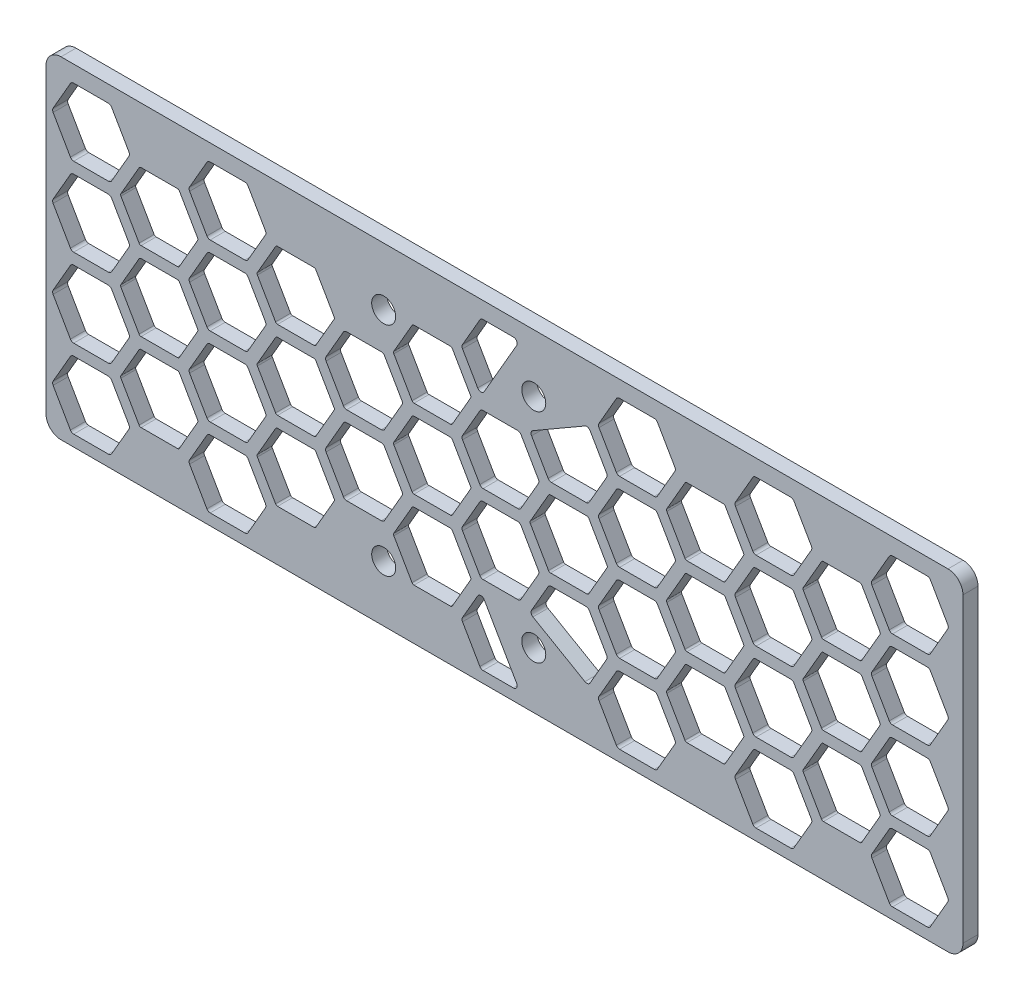
SolidWorks part; units mm, degrees
material "Thornel Mat VMA"
ref_plane "前视基准面" through (0, 0, 0) normal (0, 0, 1) x (1, 0, 0)
ref_plane "上视基准面" through (0, 0, 0) normal (0, 1, 0) x (1, 0, 0)
ref_plane "右视基准面" through (0, 0, 0) normal (1, 0, 0) x (0, 0, -1)
sketch "草图2" plane through (0, 0, 0) normal (0, 0, 1) x (1, 0, 0)
  line L89 (-79.335, -36.7) -> (-79.335, 7.5)
  line L90 (-79.335, 7.5) -> (42.865, 7.5)
  line L91 (42.865, 7.5) -> (42.865, -36.7)
  line L92 (-79.335, -36.7) -> (42.865, -36.7)
  line L120 (-41.8743, -0.2) -> (-5.6722, -0.2) construction
  line L121 (-40.735, -29.2) -> (-8.6619, -29.2) construction
  line L125 (-77.335, 3.8) -> (40.665, 3.8) construction
  line L126 (-77.335, -33.2) -> (40.665, -33.2) construction
  circle A0 centre (-34.335, -0.2) radius 1.6
  circle A1 centre (-14.335, -0.2) radius 1.6
  circle A2 centre (-34.335, -29.2) radius 1.6
  circle A3 centre (-14.335, -29.2) radius 1.6
  point P5 (-79.335, -14.6)
  point P13 (-79.335, -14.6)
  dimension "D1" = 44.2
  dimension "D19" = 4
  dimension "D21" = 20
  dimension "D22" = 20
  dimension "D23" = 45
  dimension "D24" = 45
  dimension "D25" = 3.2
  dimension "D26" = 3.2
  dimension "D27" = 3.2
  dimension "D28" = 3.2
  dimension "D2" = 122.2
  dimension "D20" = 4
extrude "凸台-拉伸1" add sketch "草图2" along normal blind 2
sketch "草图3" plane through (0, 0, 2) normal (0, 0, 1) x (1, 0, 0)
  line L0 (-79.335, -36.7) -> (42.865, -36.7) construction
  line L1 (30.7324, -20.45) -> (33.0418, -24.45)
  line L2 (33.4748, -24.7) -> (38.0936, -24.7)
  line L3 (-78.3868, -30.95) -> (-76.0774, -34.95)
  line L4 (-75.6444, -35.2) -> (-71.0256, -35.2)
  line L5 (-70.5925, -34.95) -> (-68.2831, -30.95)
  line L100 (-68.2831, -30.45) -> (-70.5925, -26.45)
  line L101 (-71.0256, -26.2) -> (-75.6444, -26.2)
  line L102 (-76.0774, -26.45) -> (-78.3868, -30.45)
  line L103 (-79.335, 7.5) -> (-79.335, -36.7) construction
  line L104 (-78.3868, -20.45) -> (-76.0774, -24.45)
  line L105 (-75.6444, -24.7) -> (-71.0256, -24.7)
  line L106 (-70.5925, -24.45) -> (-68.2831, -20.45)
  line L107 (-68.2831, -19.95) -> (-70.5925, -15.95)
  line L108 (-71.0256, -15.7) -> (-75.6444, -15.7)
  line L109 (-76.0774, -15.95) -> (-78.3868, -19.95)
  line L110 (-78.3868, -9.95) -> (-76.0774, -13.95)
  line L111 (-75.6444, -14.2) -> (-71.0256, -14.2)
  line L112 (-70.5925, -13.95) -> (-68.2831, -9.95)
  line L113 (-68.2831, -9.45) -> (-70.5925, -5.45)
  line L114 (-71.0256, -5.2) -> (-75.6444, -5.2)
  line L115 (-76.0774, -5.45) -> (-78.3868, -9.45)
  line L116 (-78.3868, 0.55) -> (-76.0774, -3.45)
  line L117 (-75.6444, -3.7) -> (-71.0256, -3.7)
  line L118 (-70.5925, -3.45) -> (-68.2831, 0.55)
  line L119 (-68.2831, 1.05) -> (-70.5925, 5.05)
  line L120 (-71.0256, 5.3) -> (-75.6444, 5.3)
  line L121 (-76.0774, 5.05) -> (-78.3868, 1.05)
  line L128 (-69.3504, -15.1015) -> (-66.9272, -19.2985)
  line L129 (-69.3504, -25.6015) -> (-66.9272, -29.7985)
  line L130 (-66.6648, -29.95) -> (-61.8186, -29.95)
  line L131 (-61.5561, -29.7985) -> (-59.133, -25.6015)
  line L132 (-59.133, -25.2985) -> (-61.5561, -21.1015)
  line L133 (-61.8186, -20.95) -> (-66.6648, -20.95)
  line L134 (-66.9272, -21.1015) -> (-69.3504, -25.2985)
  line L135 (-66.6648, -19.45) -> (-61.8186, -19.45)
  line L136 (-61.5561, -19.2985) -> (-59.133, -15.1015)
  line L137 (-59.133, -14.7985) -> (-61.5561, -10.6015)
  line L138 (-61.8186, -10.45) -> (-66.6648, -10.45)
  line L139 (-66.9272, -10.6015) -> (-69.3504, -14.7985)
  line L140 (-69.3504, -4.6015) -> (-66.9272, -8.7985)
  line L141 (-66.6648, -8.95) -> (-61.8186, -8.95)
  line L142 (-61.5561, -8.7985) -> (-59.133, -4.6015)
  line L143 (-59.133, -4.2985) -> (-61.5561, -0.1015)
  line L144 (-61.8186, 0.05) -> (-66.6648, 0.05)
  line L145 (-66.9272, -0.1015) -> (-69.3504, -4.2985)
  line L146 (-60.2002, -30.95) -> (-57.8908, -34.95)
  line L147 (-57.4578, -35.2) -> (-52.839, -35.2)
  line L148 (-52.406, -34.95) -> (-50.0966, -30.95)
  line L149 (-50.0966, -30.45) -> (-52.406, -26.45)
  line L150 (-52.839, -26.2) -> (-57.4578, -26.2)
  line L151 (-57.8908, -26.45) -> (-60.2002, -30.45)
  line L152 (-60.2002, -20.45) -> (-57.8908, -24.45)
  line L153 (-57.4578, -24.7) -> (-52.839, -24.7)
  line L154 (-52.406, -24.45) -> (-50.0966, -20.45)
  line L155 (-50.0966, -19.95) -> (-52.406, -15.95)
  line L156 (-52.839, -15.7) -> (-57.4578, -15.7)
  line L157 (-57.8908, -15.95) -> (-60.2002, -19.95)
  line L158 (-60.2002, -9.95) -> (-57.8908, -13.95)
  line L159 (-57.4578, -14.2) -> (-52.839, -14.2)
  line L160 (-52.406, -13.95) -> (-50.0966, -9.95)
  line L161 (-50.0966, -9.45) -> (-52.406, -5.45)
  line L162 (-52.839, -5.2) -> (-57.4578, -5.2)
  line L163 (-57.8908, -5.45) -> (-60.2002, -9.45)
  line L164 (-60.2002, 0.55) -> (-57.8908, -3.45)
  line L165 (-57.4578, -3.7) -> (-52.839, -3.7)
  line L166 (-52.406, -3.45) -> (-50.0966, 0.55)
  line L167 (-50.0966, 1.05) -> (-52.406, 5.05)
  line L168 (-52.839, 5.3) -> (-57.4578, 5.3)
  line L169 (-57.8908, 5.05) -> (-60.2002, 1.05)
  line L170 (-51.1638, -15.1015) -> (-48.7407, -19.2985)
  line L171 (-51.1638, -25.6015) -> (-48.7407, -29.7985)
  line L172 (-48.4783, -29.95) -> (-43.632, -29.95)
  line L173 (-43.3696, -29.7985) -> (-40.9465, -25.6015)
  line L174 (-40.9465, -25.2985) -> (-43.3696, -21.1015)
  line L175 (-43.632, -20.95) -> (-48.4783, -20.95)
  line L176 (-48.7407, -21.1015) -> (-51.1638, -25.2985)
  line L177 (-48.4783, -19.45) -> (-43.632, -19.45)
  line L178 (-43.3696, -19.2985) -> (-40.9465, -15.1015)
  line L179 (-40.9465, -14.7985) -> (-43.3696, -10.6015)
  line L180 (-43.632, -10.45) -> (-48.4783, -10.45)
  line L181 (-48.7407, -10.6015) -> (-51.1638, -14.7985)
  line L182 (-51.1638, -4.6015) -> (-48.7407, -8.7985)
  line L183 (-48.4783, -8.95) -> (-43.632, -8.95)
  line L184 (-43.3696, -8.7985) -> (-40.9465, -4.6015)
  line L185 (-40.9465, -4.2985) -> (-43.3696, -0.1015)
  line L186 (-43.632, 0.05) -> (-48.4783, 0.05)
  line L187 (-48.7407, -0.1015) -> (-51.1638, -4.2985)
  line L194 (-42.0137, -20.45) -> (-39.7043, -24.45)
  line L195 (-39.2713, -24.7) -> (-34.6525, -24.7)
  line L196 (-34.2195, -24.45) -> (-31.9101, -20.45)
  line L197 (-31.9101, -19.95) -> (-34.2195, -15.95)
  line L198 (-34.6525, -15.7) -> (-39.2713, -15.7)
  line L199 (-39.7043, -15.95) -> (-42.0137, -19.95)
  line L200 (-42.0137, -9.95) -> (-39.7043, -13.95)
  line L201 (-39.2713, -14.2) -> (-34.6525, -14.2)
  line L202 (-34.2195, -13.95) -> (-31.9101, -9.95)
  line L203 (-31.9101, -9.45) -> (-34.2195, -5.45)
  line L204 (-34.6525, -5.2) -> (-39.2713, -5.2)
  line L205 (-39.7043, -5.45) -> (-42.0137, -9.45)
  line L212 (-32.9773, -15.1015) -> (-30.5542, -19.2985)
  line L213 (-32.9773, -25.6015) -> (-30.5542, -29.7985)
  line L214 (-30.2918, -29.95) -> (-25.4455, -29.95)
  line L215 (-25.1831, -29.7985) -> (-22.7599, -25.6015)
  line L216 (-22.7599, -25.2985) -> (-25.1831, -21.1015)
  line L217 (-25.4455, -20.95) -> (-30.2918, -20.95)
  line L218 (-30.5542, -21.1015) -> (-32.9773, -25.2985)
  line L219 (-30.2918, -19.45) -> (-25.4455, -19.45)
  line L220 (-25.1831, -19.2985) -> (-22.7599, -15.1015)
  line L221 (-22.7599, -14.7985) -> (-25.1831, -10.6015)
  line L222 (-25.4455, -10.45) -> (-30.2918, -10.45)
  line L223 (-30.5542, -10.6015) -> (-32.9773, -14.7985)
  line L224 (-32.9773, -4.6015) -> (-30.5542, -8.7985)
  line L225 (-30.2918, -8.95) -> (-25.4455, -8.95)
  line L226 (-25.1831, -8.7985) -> (-22.7599, -4.6015)
  line L227 (-22.7599, -4.2985) -> (-25.1831, -0.1015)
  line L228 (-25.4455, 0.05) -> (-30.2918, 0.05)
  line L229 (-30.5542, -0.1015) -> (-32.9773, -4.2985)
  line L236 (-23.8272, -20.45) -> (-21.5178, -24.45)
  line L237 (-21.0848, -24.7) -> (-16.466, -24.7)
  line L238 (-16.0329, -24.45) -> (-13.7235, -20.45)
  line L239 (-13.7235, -19.95) -> (-16.0329, -15.95)
  line L240 (-16.466, -15.7) -> (-21.0848, -15.7)
  line L241 (-21.5178, -15.95) -> (-23.8272, -19.95)
  line L242 (-23.8272, -9.95) -> (-21.5178, -13.95)
  line L243 (-21.0848, -14.2) -> (-16.466, -14.2)
  line L244 (-16.0329, -13.95) -> (-13.7235, -9.95)
  line L245 (-13.7235, -9.45) -> (-16.0329, -5.45)
  line L246 (-16.466, -5.2) -> (-21.0848, -5.2)
  line L247 (-21.5178, -5.45) -> (-23.8272, -9.45)
  line L254 (-14.7908, -15.1015) -> (-12.3676, -19.2985)
  line L261 (-12.1052, -19.45) -> (-7.259, -19.45)
  line L262 (-6.9965, -19.2985) -> (-4.5734, -15.1015)
  line L263 (-4.5734, -14.7985) -> (-6.9965, -10.6015)
  line L264 (-7.259, -10.45) -> (-12.1052, -10.45)
  line L265 (-12.3676, -10.6015) -> (-14.7908, -14.7985)
  line L272 (-5.6406, -30.95) -> (-3.3312, -34.95)
  line L273 (-2.8982, -35.2) -> (1.7206, -35.2)
  line L274 (2.1536, -34.95) -> (4.463, -30.95)
  line L275 (4.463, -30.45) -> (2.1536, -26.45)
  line L276 (1.7206, -26.2) -> (-2.8982, -26.2)
  line L277 (-3.3312, -26.45) -> (-5.6406, -30.45)
  line L278 (-5.6406, -20.45) -> (-3.3312, -24.45)
  line L279 (-2.8982, -24.7) -> (1.7206, -24.7)
  line L280 (2.1536, -24.45) -> (4.463, -20.45)
  line L281 (4.463, -19.95) -> (2.1536, -15.95)
  line L282 (1.7206, -15.7) -> (-2.8982, -15.7)
  line L283 (-3.3312, -15.95) -> (-5.6406, -19.95)
  line L284 (-5.6406, -9.95) -> (-3.3312, -13.95)
  line L285 (-2.8982, -14.2) -> (1.7206, -14.2)
  line L286 (2.1536, -13.95) -> (4.463, -9.95)
  line L287 (4.463, -9.45) -> (2.1536, -5.45)
  line L288 (1.7206, -5.2) -> (-2.8982, -5.2)
  line L289 (-3.3312, -5.45) -> (-5.6406, -9.45)
  line L290 (-5.6406, 0.55) -> (-3.3312, -3.45)
  line L291 (-2.8982, -3.7) -> (1.7206, -3.7)
  line L292 (2.1536, -3.45) -> (4.463, 0.55)
  line L293 (4.463, 1.05) -> (2.1536, 5.05)
  line L294 (1.7206, 5.3) -> (-2.8982, 5.3)
  line L295 (-3.3312, 5.05) -> (-5.6406, 1.05)
  line L296 (3.3958, -15.1015) -> (5.8189, -19.2985)
  line L297 (3.3958, -25.6015) -> (5.8189, -29.7985)
  line L298 (6.0813, -29.95) -> (10.9276, -29.95)
  line L299 (11.19, -29.7985) -> (13.6131, -25.6015)
  line L300 (13.6131, -25.2985) -> (11.19, -21.1015)
  line L301 (10.9276, -20.95) -> (6.0813, -20.95)
  line L302 (5.8189, -21.1015) -> (3.3958, -25.2985)
  line L303 (6.0813, -19.45) -> (10.9276, -19.45)
  line L304 (11.19, -19.2985) -> (13.6131, -15.1015)
  line L305 (13.6131, -14.7985) -> (11.19, -10.6015)
  line L306 (10.9276, -10.45) -> (6.0813, -10.45)
  line L307 (5.8189, -10.6015) -> (3.3958, -14.7985)
  line L308 (3.3958, -4.6015) -> (5.8189, -8.7985)
  line L309 (6.0813, -8.95) -> (10.9276, -8.95)
  line L310 (11.19, -8.7985) -> (13.6131, -4.6015)
  line L311 (13.6131, -4.2985) -> (11.19, -0.1015)
  line L312 (10.9276, 0.05) -> (6.0813, 0.05)
  line L313 (5.8189, -0.1015) -> (3.3958, -4.2985)
  line L314 (12.5459, -30.95) -> (14.8553, -34.95)
  line L315 (15.2883, -35.2) -> (19.9071, -35.2)
  line L316 (20.3401, -34.95) -> (22.6495, -30.95)
  line L317 (22.6495, -30.45) -> (20.3401, -26.45)
  line L318 (19.9071, -26.2) -> (15.2883, -26.2)
  line L319 (14.8553, -26.45) -> (12.5459, -30.45)
  line L320 (12.5459, -20.45) -> (14.8553, -24.45)
  line L321 (15.2883, -24.7) -> (19.9071, -24.7)
  line L322 (20.3401, -24.45) -> (22.6495, -20.45)
  line L323 (22.6495, -19.95) -> (20.3401, -15.95)
  line L324 (19.9071, -15.7) -> (15.2883, -15.7)
  line L325 (14.8553, -15.95) -> (12.5459, -19.95)
  line L326 (12.5459, -9.95) -> (14.8553, -13.95)
  line L327 (15.2883, -14.2) -> (19.9071, -14.2)
  line L328 (20.3401, -13.95) -> (22.6495, -9.95)
  line L329 (22.6495, -9.45) -> (20.3401, -5.45)
  line L330 (19.9071, -5.2) -> (15.2883, -5.2)
  line L331 (14.8553, -5.45) -> (12.5459, -9.45)
  line L332 (12.5459, 0.55) -> (14.8553, -3.45)
  line L333 (15.2883, -3.7) -> (19.9071, -3.7)
  line L334 (20.3401, -3.45) -> (22.6495, 0.55)
  line L335 (22.6495, 1.05) -> (20.3401, 5.05)
  line L336 (19.9071, 5.3) -> (15.2883, 5.3)
  line L337 (14.8553, 5.05) -> (12.5459, 1.05)
  line L338 (21.5823, -15.1015) -> (24.0054, -19.2985)
  line L339 (21.5823, -25.6015) -> (24.0054, -29.7985)
  line L340 (24.2678, -29.95) -> (29.1141, -29.95)
  line L341 (29.3765, -29.7985) -> (31.7997, -25.6015)
  line L342 (31.7997, -25.2985) -> (29.3765, -21.1015)
  line L343 (29.1141, -20.95) -> (24.2678, -20.95)
  line L344 (24.0054, -21.1015) -> (21.5823, -25.2985)
  line L345 (24.2678, -19.45) -> (29.1141, -19.45)
  line L346 (29.3765, -19.2985) -> (31.7997, -15.1015)
  line L347 (31.7997, -14.7985) -> (29.3765, -10.6015)
  line L348 (29.1141, -10.45) -> (24.2678, -10.45)
  line L349 (24.0054, -10.6015) -> (21.5823, -14.7985)
  line L350 (21.5823, -4.6015) -> (24.0054, -8.7985)
  line L351 (24.2678, -8.95) -> (29.1141, -8.95)
  line L352 (29.3765, -8.7985) -> (31.7997, -4.6015)
  line L353 (31.7997, -4.2985) -> (29.3765, -0.1015)
  line L354 (29.1141, 0.05) -> (24.2678, 0.05)
  line L355 (24.0054, -0.1015) -> (21.5823, -4.2985)
  line L356 (38.5267, -24.45) -> (40.8361, -20.45)
  line L363 (30.7324, -30.95) -> (33.0418, -34.95)
  line L364 (33.4748, -35.2) -> (38.0936, -35.2)
  line L365 (38.5267, -34.95) -> (40.8361, -30.95)
  line L366 (40.8361, -30.45) -> (38.5267, -26.45)
  line L367 (38.0936, -26.2) -> (33.4748, -26.2)
  line L368 (33.0418, -26.45) -> (30.7324, -30.45)
  line L369 (40.8361, -19.95) -> (38.5267, -15.95)
  line L370 (38.0936, -15.7) -> (33.4748, -15.7)
  line L371 (33.0418, -15.95) -> (30.7324, -19.95)
  line L372 (30.7324, -9.95) -> (33.0418, -13.95)
  line L373 (33.4748, -14.2) -> (38.0936, -14.2)
  line L374 (38.5267, -13.95) -> (40.8361, -9.95)
  line L375 (40.8361, -9.45) -> (38.5267, -5.45)
  line L376 (38.0936, -5.2) -> (33.4748, -5.2)
  line L377 (33.0418, -5.45) -> (30.7324, -9.45)
  line L378 (30.7324, 0.55) -> (33.0418, -3.45)
  line L379 (33.4748, -3.7) -> (38.0936, -3.7)
  line L380 (38.5267, -3.45) -> (40.8361, 0.55)
  line L381 (40.8361, 1.05) -> (38.5267, 5.05)
  line L382 (38.0936, 5.3) -> (33.4748, 5.3)
  line L383 (33.0418, 5.05) -> (30.7324, 1.05)
  line L384 (-42.0137, 0.55) -> (-39.7043, -3.45) [skipped]
  line L385 (-39.2713, -3.7) -> (-34.6525, -3.7) [skipped]
  line L386 (-34.2195, -3.45) -> (-31.9101, 0.55) [skipped]
  line L387 (-31.9101, 1.05) -> (-34.2195, 5.05) [skipped]
  line L388 (-34.6525, 5.3) -> (-39.2713, 5.3) [skipped]
  line L389 (-39.7043, 5.05) -> (-42.0137, 1.05) [skipped]
  line L390 (-42.0137, -30.95) -> (-39.7043, -34.95) [skipped]
  line L391 (-39.2713, -35.2) -> (-34.6525, -35.2) [skipped]
  line L392 (-34.2195, -34.95) -> (-31.9101, -30.95) [skipped]
  line L393 (-31.9101, -30.45) -> (-34.2195, -26.45) [skipped]
  line L394 (-34.6525, -26.2) -> (-39.2713, -26.2) [skipped]
  line L395 (-39.7043, -26.45) -> (-42.0137, -30.45) [skipped]
  line L396 (-23.8272, -30.95) -> (-21.5178, -34.95) [skipped]
  line L397 (-21.0848, -35.2) -> (-16.466, -35.2) [skipped]
  line L398 (-16.0329, -34.95) -> (-13.7235, -30.95) [skipped]
  line L399 (-13.7235, -30.45) -> (-16.0329, -26.45) [skipped]
  line L400 (-16.466, -26.2) -> (-21.0848, -26.2) [skipped]
  line L401 (-21.5178, -26.45) -> (-23.8272, -30.45) [skipped]
  line L402 (-14.7908, -25.6015) -> (-12.3676, -29.7985) [skipped]
  line L403 (-12.1052, -29.95) -> (-7.259, -29.95) [skipped]
  line L404 (-6.9965, -29.7985) -> (-4.5734, -25.6015) [skipped]
  line L405 (-4.5734, -25.2985) -> (-6.9965, -21.1015) [skipped]
  line L406 (-7.259, -20.95) -> (-12.1052, -20.95) [skipped]
  line L407 (-12.3676, -21.1015) -> (-14.7908, -25.2985) [skipped]
  line L408 (-20.9404, -26.95) -> (-16.6103, -34.45)
  line L409 (-23.8272, -30.95) -> (-21.5178, -34.95)
  line L410 (-21.0848, -35.2) -> (-17.0433, -35.2)
  line L414 (-21.8064, -26.95) -> (-23.8272, -30.45)
  line L415 (-14.4452, -25.7) -> (-7.517, -29.7)
  line L416 (-16.1773, -26.2) -> (-18.7754, -26.2) [skipped]
  line L417 (-13.5792, -30.7) -> (-14.8782, -28.45) [skipped]
  line L418 (-16.1773, -35.2) -> (-14.8782, -32.95) [skipped]
  line L421 (-6.834, -29.517) -> (-4.6303, -25.7)
  line L422 (-4.6303, -25.2) -> (-6.9397, -21.2)
  line L423 (-7.3727, -20.95) -> (-11.9915, -20.95)
  line L424 (-12.4245, -21.2) -> (-14.6282, -25.017)
  line L425 (-69.391, -14.95) -> (-59.0924, -14.95) construction
  line L426 (-13.5792, -27.7) -> (-12.2802, -29.95) [skipped]
  line L427 (-9.6821, -29.95) -> (-7.084, -29.95) [skipped]
  line L428 (-23.8272, 0.55) -> (-21.5178, -3.45) [skipped]
  line L429 (-21.0848, -3.7) -> (-16.466, -3.7) [skipped]
  line L430 (-16.0329, -3.45) -> (-13.7235, 0.55) [skipped]
  line L431 (-13.7235, 1.05) -> (-16.0329, 5.05) [skipped]
  line L432 (-16.466, 5.3) -> (-21.0848, 5.3) [skipped]
  line L433 (-21.5178, 5.05) -> (-23.8272, 1.05) [skipped]
  line L434 (-14.7908, -4.6015) -> (-12.3676, -8.7985) [skipped]
  line L435 (-12.1052, -8.95) -> (-7.259, -8.95) [skipped]
  line L436 (-6.9965, -8.7985) -> (-4.5734, -4.6015) [skipped]
  line L437 (-4.5734, -4.2985) -> (-6.9965, -0.1015) [skipped]
  line L438 (-7.259, 0.05) -> (-12.1052, 0.05) [skipped]
  line L439 (-12.3676, -0.1015) -> (-14.7908, -4.2985) [skipped]
  line L440 (-21.8064, -2.95) -> (-23.8272, 0.55)
  line L441 (-23.8272, 1.05) -> (-21.5178, 5.05)
  line L442 (-21.0848, 5.3) -> (-17.0433, 5.3)
  line L443 (-20.9404, -2.95) -> (-16.6103, 4.55)
  line L444 (-12.4245, -8.7) -> (-14.6282, -4.883)
  line L445 (-7.3727, -8.95) -> (-11.9915, -8.95)
  line L446 (-4.6303, -4.7) -> (-6.9397, -8.7)
  line L447 (-6.834, -0.383) -> (-4.6303, -4.2)
  line L448 (-14.4452, -4.2) -> (-7.517, -0.2)
  circle A0 centre (-73.335, -30.7) radius 4.5 construction
  arc A1 (-78.3868, -30.95) -> (-78.3868, -30.45) centre (-77.9538, -30.7) cw
  arc A2 (-76.0774, -34.95) -> (-75.6444, -35.2) centre (-75.6444, -34.7) ccw
  arc A3 (-71.0256, -35.2) -> (-70.5925, -34.95) centre (-71.0256, -34.7) ccw
  arc A14 (-68.2831, -30.95) -> (-68.2831, -30.45) centre (-68.7162, -30.7) ccw
  arc A15 (-70.5925, -26.45) -> (-71.0256, -26.2) centre (-71.0256, -26.7) ccw
  arc A16 (-75.6444, -26.2) -> (-76.0774, -26.45) centre (-75.6444, -26.7) ccw
  arc A17 (-78.3868, -20.45) -> (-78.3868, -19.95) centre (-77.9538, -20.2) cw
  arc A18 (-76.0774, -24.45) -> (-75.6444, -24.7) centre (-75.6444, -24.2) ccw
  arc A19 (-71.0256, -24.7) -> (-70.5925, -24.45) centre (-71.0256, -24.2) ccw
  arc A20 (-68.2831, -20.45) -> (-68.2831, -19.95) centre (-68.7162, -20.2) ccw
  arc A21 (-70.5925, -15.95) -> (-71.0256, -15.7) centre (-71.0256, -16.2) ccw
  arc A22 (-75.6444, -15.7) -> (-76.0774, -15.95) centre (-75.6444, -16.2) ccw
  circle A23 centre (-73.335, -20.2) radius 4.5 construction
  arc A24 (-78.3868, -9.95) -> (-78.3868, -9.45) centre (-77.9538, -9.7) cw
  arc A25 (-76.0774, -13.95) -> (-75.6444, -14.2) centre (-75.6444, -13.7) ccw
  arc A26 (-71.0256, -14.2) -> (-70.5925, -13.95) centre (-71.0256, -13.7) ccw
  arc A27 (-68.2831, -9.95) -> (-68.2831, -9.45) centre (-68.7162, -9.7) ccw
  arc A28 (-70.5925, -5.45) -> (-71.0256, -5.2) centre (-71.0256, -5.7) ccw
  arc A29 (-75.6444, -5.2) -> (-76.0774, -5.45) centre (-75.6444, -5.7) ccw
  circle A30 centre (-73.335, -9.7) radius 4.5 construction
  arc A31 (-78.3868, 0.55) -> (-78.3868, 1.05) centre (-77.9538, 0.8) cw
  arc A32 (-76.0774, -3.45) -> (-75.6444, -3.7) centre (-75.6444, -3.2) ccw
  arc A33 (-71.0256, -3.7) -> (-70.5925, -3.45) centre (-71.0256, -3.2) ccw
  arc A34 (-68.2831, 0.55) -> (-68.2831, 1.05) centre (-68.7162, 0.8) ccw
  arc A35 (-70.5925, 5.05) -> (-71.0256, 5.3) centre (-71.0256, 4.8) ccw
  arc A36 (-75.6444, 5.3) -> (-76.0774, 5.05) centre (-75.6444, 4.8) ccw
  circle A37 centre (-73.335, 0.8) radius 4.5 construction
  circle A44 centre (-64.2417, -25.45) radius 4.5 construction
  arc A45 (-66.9272, -29.7985) -> (-66.6648, -29.95) centre (-66.6648, -29.647) ccw
  arc A46 (-61.8186, -29.95) -> (-61.5561, -29.7985) centre (-61.8186, -29.647) ccw
  arc A47 (-59.133, -25.6015) -> (-59.133, -25.2985) centre (-59.3954, -25.45) ccw
  arc A48 (-61.5561, -21.1015) -> (-61.8186, -20.95) centre (-61.8186, -21.253) ccw
  arc A49 (-66.6648, -20.95) -> (-66.9272, -21.1015) centre (-66.6648, -21.253) ccw
  arc A50 (-69.3504, -25.6015) -> (-69.3504, -25.2985) centre (-69.088, -25.45) cw
  arc A51 (-69.3504, -15.1015) -> (-69.3504, -14.7985) centre (-69.088, -14.95) cw
  arc A52 (-66.9272, -19.2985) -> (-66.6648, -19.45) centre (-66.6648, -19.147) ccw
  arc A53 (-61.8186, -19.45) -> (-61.5561, -19.2985) centre (-61.8186, -19.147) ccw
  arc A54 (-59.133, -15.1015) -> (-59.133, -14.7985) centre (-59.3954, -14.95) ccw
  arc A55 (-61.5561, -10.6015) -> (-61.8186, -10.45) centre (-61.8186, -10.753) ccw
  arc A56 (-66.6648, -10.45) -> (-66.9272, -10.6015) centre (-66.6648, -10.753) ccw
  arc A57 (-69.3504, -4.6015) -> (-69.3504, -4.2985) centre (-69.088, -4.45) cw
  arc A58 (-66.9272, -8.7985) -> (-66.6648, -8.95) centre (-66.6648, -8.647) ccw
  arc A59 (-61.8186, -8.95) -> (-61.5561, -8.7985) centre (-61.8186, -8.647) ccw
  arc A60 (-59.133, -4.6015) -> (-59.133, -4.2985) centre (-59.3954, -4.45) ccw
  arc A61 (-61.5561, -0.1015) -> (-61.8186, 0.05) centre (-61.8186, -0.253) ccw
  arc A62 (-66.6648, 0.05) -> (-66.9272, -0.1015) centre (-66.6648, -0.253) ccw
  arc A63 (-60.2002, -30.95) -> (-60.2002, -30.45) centre (-59.7672, -30.7) cw
  arc A64 (-57.8908, -34.95) -> (-57.4578, -35.2) centre (-57.4578, -34.7) ccw
  arc A65 (-52.839, -35.2) -> (-52.406, -34.95) centre (-52.839, -34.7) ccw
  arc A66 (-50.0966, -30.95) -> (-50.0966, -30.45) centre (-50.5296, -30.7) ccw
  arc A67 (-52.406, -26.45) -> (-52.839, -26.2) centre (-52.839, -26.7) ccw
  arc A68 (-57.4578, -26.2) -> (-57.8908, -26.45) centre (-57.4578, -26.7) ccw
  arc A69 (-60.2002, -20.45) -> (-60.2002, -19.95) centre (-59.7672, -20.2) cw
  arc A70 (-57.8908, -24.45) -> (-57.4578, -24.7) centre (-57.4578, -24.2) ccw
  arc A71 (-52.839, -24.7) -> (-52.406, -24.45) centre (-52.839, -24.2) ccw
  arc A72 (-50.0966, -20.45) -> (-50.0966, -19.95) centre (-50.5296, -20.2) ccw
  arc A73 (-52.406, -15.95) -> (-52.839, -15.7) centre (-52.839, -16.2) ccw
  arc A74 (-57.4578, -15.7) -> (-57.8908, -15.95) centre (-57.4578, -16.2) ccw
  arc A75 (-60.2002, -9.95) -> (-60.2002, -9.45) centre (-59.7672, -9.7) cw
  arc A76 (-57.8908, -13.95) -> (-57.4578, -14.2) centre (-57.4578, -13.7) ccw
  arc A77 (-52.839, -14.2) -> (-52.406, -13.95) centre (-52.839, -13.7) ccw
  arc A78 (-50.0966, -9.95) -> (-50.0966, -9.45) centre (-50.5296, -9.7) ccw
  arc A79 (-52.406, -5.45) -> (-52.839, -5.2) centre (-52.839, -5.7) ccw
  arc A80 (-57.4578, -5.2) -> (-57.8908, -5.45) centre (-57.4578, -5.7) ccw
  arc A81 (-60.2002, 0.55) -> (-60.2002, 1.05) centre (-59.7672, 0.8) cw
  arc A82 (-57.8908, -3.45) -> (-57.4578, -3.7) centre (-57.4578, -3.2) ccw
  arc A83 (-52.839, -3.7) -> (-52.406, -3.45) centre (-52.839, -3.2) ccw
  arc A84 (-50.0966, 0.55) -> (-50.0966, 1.05) centre (-50.5296, 0.8) ccw
  arc A85 (-52.406, 5.05) -> (-52.839, 5.3) centre (-52.839, 4.8) ccw
  arc A86 (-57.4578, 5.3) -> (-57.8908, 5.05) centre (-57.4578, 4.8) ccw
  arc A87 (-48.7407, -29.7985) -> (-48.4783, -29.95) centre (-48.4783, -29.647) ccw
  arc A88 (-43.632, -29.95) -> (-43.3696, -29.7985) centre (-43.632, -29.647) ccw
  arc A89 (-40.9465, -25.6015) -> (-40.9465, -25.2985) centre (-41.2089, -25.45) ccw
  arc A90 (-43.3696, -21.1015) -> (-43.632, -20.95) centre (-43.632, -21.253) ccw
  arc A91 (-48.4783, -20.95) -> (-48.7407, -21.1015) centre (-48.4783, -21.253) ccw
  arc A92 (-51.1638, -25.6015) -> (-51.1638, -25.2985) centre (-50.9014, -25.45) cw
  arc A93 (-51.1638, -15.1015) -> (-51.1638, -14.7985) centre (-50.9014, -14.95) cw
  arc A94 (-48.7407, -19.2985) -> (-48.4783, -19.45) centre (-48.4783, -19.147) ccw
  arc A95 (-43.632, -19.45) -> (-43.3696, -19.2985) centre (-43.632, -19.147) ccw
  arc A96 (-40.9465, -15.1015) -> (-40.9465, -14.7985) centre (-41.2089, -14.95) ccw
  arc A97 (-43.3696, -10.6015) -> (-43.632, -10.45) centre (-43.632, -10.753) ccw
  arc A98 (-48.4783, -10.45) -> (-48.7407, -10.6015) centre (-48.4783, -10.753) ccw
  arc A99 (-51.1638, -4.6015) -> (-51.1638, -4.2985) centre (-50.9014, -4.45) cw
  arc A100 (-48.7407, -8.7985) -> (-48.4783, -8.95) centre (-48.4783, -8.647) ccw
  arc A101 (-43.632, -8.95) -> (-43.3696, -8.7985) centre (-43.632, -8.647) ccw
  arc A102 (-40.9465, -4.6015) -> (-40.9465, -4.2985) centre (-41.2089, -4.45) ccw
  arc A103 (-43.3696, -0.1015) -> (-43.632, 0.05) centre (-43.632, -0.253) ccw
  arc A104 (-48.4783, 0.05) -> (-48.7407, -0.1015) centre (-48.4783, -0.253) ccw
  circle A105 centre (-55.1484, -30.7) radius 4.5 construction
  circle A106 centre (-55.1484, -20.2) radius 4.5 construction
  circle A107 centre (-55.1484, -9.7) radius 4.5 construction
  circle A108 centre (-55.1484, 0.8) radius 4.5 construction
  circle A109 centre (-46.0552, -25.45) radius 4.5 construction
  arc A116 (-42.0137, -20.45) -> (-42.0137, -19.95) centre (-41.5807, -20.2) cw
  arc A117 (-39.7043, -24.45) -> (-39.2713, -24.7) centre (-39.2713, -24.2) ccw
  arc A118 (-34.6525, -24.7) -> (-34.2195, -24.45) centre (-34.6525, -24.2) ccw
  arc A119 (-31.9101, -20.45) -> (-31.9101, -19.95) centre (-32.3431, -20.2) ccw
  arc A120 (-34.2195, -15.95) -> (-34.6525, -15.7) centre (-34.6525, -16.2) ccw
  arc A121 (-39.2713, -15.7) -> (-39.7043, -15.95) centre (-39.2713, -16.2) ccw
  arc A122 (-42.0137, -9.95) -> (-42.0137, -9.45) centre (-41.5807, -9.7) cw
  arc A123 (-39.7043, -13.95) -> (-39.2713, -14.2) centre (-39.2713, -13.7) ccw
  arc A124 (-34.6525, -14.2) -> (-34.2195, -13.95) centre (-34.6525, -13.7) ccw
  arc A125 (-31.9101, -9.95) -> (-31.9101, -9.45) centre (-32.3431, -9.7) ccw
  arc A126 (-34.2195, -5.45) -> (-34.6525, -5.2) centre (-34.6525, -5.7) ccw
  arc A127 (-39.2713, -5.2) -> (-39.7043, -5.45) centre (-39.2713, -5.7) ccw
  arc A134 (-30.5542, -29.7985) -> (-30.2918, -29.95) centre (-30.2918, -29.647) ccw
  arc A135 (-25.4455, -29.95) -> (-25.1831, -29.7985) centre (-25.4455, -29.647) ccw
  arc A136 (-22.7599, -25.6015) -> (-22.7599, -25.2985) centre (-23.0224, -25.45) ccw
  arc A137 (-25.1831, -21.1015) -> (-25.4455, -20.95) centre (-25.4455, -21.253) ccw
  arc A138 (-30.2918, -20.95) -> (-30.5542, -21.1015) centre (-30.2918, -21.253) ccw
  arc A139 (-32.9773, -25.6015) -> (-32.9773, -25.2985) centre (-32.7149, -25.45) cw
  arc A140 (-32.9773, -15.1015) -> (-32.9773, -14.7985) centre (-32.7149, -14.95) cw
  arc A141 (-30.5542, -19.2985) -> (-30.2918, -19.45) centre (-30.2918, -19.147) ccw
  arc A142 (-25.4455, -19.45) -> (-25.1831, -19.2985) centre (-25.4455, -19.147) ccw
  arc A143 (-22.7599, -15.1015) -> (-22.7599, -14.7985) centre (-23.0224, -14.95) ccw
  arc A144 (-25.1831, -10.6015) -> (-25.4455, -10.45) centre (-25.4455, -10.753) ccw
  arc A145 (-30.2918, -10.45) -> (-30.5542, -10.6015) centre (-30.2918, -10.753) ccw
  arc A146 (-32.9773, -4.6015) -> (-32.9773, -4.2985) centre (-32.7149, -4.45) cw
  arc A147 (-30.5542, -8.7985) -> (-30.2918, -8.95) centre (-30.2918, -8.647) ccw
  arc A148 (-25.4455, -8.95) -> (-25.1831, -8.7985) centre (-25.4455, -8.647) ccw
  arc A149 (-22.7599, -4.6015) -> (-22.7599, -4.2985) centre (-23.0224, -4.45) ccw
  arc A150 (-25.1831, -0.1015) -> (-25.4455, 0.05) centre (-25.4455, -0.253) ccw
  arc A151 (-30.2918, 0.05) -> (-30.5542, -0.1015) centre (-30.2918, -0.253) ccw
  circle A152 centre (-36.9619, -30.7) radius 4.5 construction
  circle A153 centre (-36.9619, -20.2) radius 4.5 construction
  circle A154 centre (-36.9619, -9.7) radius 4.5 construction
  circle A155 centre (-36.9619, 0.8) radius 4.5 construction
  circle A156 centre (-27.8686, -25.45) radius 4.5 construction
  arc A163 (-23.8272, -20.45) -> (-23.8272, -19.95) centre (-23.3942, -20.2) cw
  arc A164 (-21.5178, -24.45) -> (-21.0848, -24.7) centre (-21.0848, -24.2) ccw
  arc A165 (-16.466, -24.7) -> (-16.0329, -24.45) centre (-16.466, -24.2) ccw
  arc A166 (-13.7235, -20.45) -> (-13.7235, -19.95) centre (-14.1566, -20.2) ccw
  arc A167 (-16.0329, -15.95) -> (-16.466, -15.7) centre (-16.466, -16.2) ccw
  arc A168 (-21.0848, -15.7) -> (-21.5178, -15.95) centre (-21.0848, -16.2) ccw
  arc A169 (-23.8272, -9.95) -> (-23.8272, -9.45) centre (-23.3942, -9.7) cw
  arc A170 (-21.5178, -13.95) -> (-21.0848, -14.2) centre (-21.0848, -13.7) ccw
  arc A171 (-16.466, -14.2) -> (-16.0329, -13.95) centre (-16.466, -13.7) ccw
  arc A172 (-13.7235, -9.95) -> (-13.7235, -9.45) centre (-14.1566, -9.7) ccw
  arc A173 (-16.0329, -5.45) -> (-16.466, -5.2) centre (-16.466, -5.7) ccw
  arc A174 (-21.0848, -5.2) -> (-21.5178, -5.45) centre (-21.0848, -5.7) ccw
  arc A187 (-14.7908, -15.1015) -> (-14.7908, -14.7985) centre (-14.5284, -14.95) cw
  arc A188 (-12.3676, -19.2985) -> (-12.1052, -19.45) centre (-12.1052, -19.147) ccw
  arc A189 (-7.259, -19.45) -> (-6.9965, -19.2985) centre (-7.259, -19.147) ccw
  arc A190 (-4.5734, -15.1015) -> (-4.5734, -14.7985) centre (-4.8358, -14.95) ccw
  arc A191 (-6.9965, -10.6015) -> (-7.259, -10.45) centre (-7.259, -10.753) ccw
  arc A192 (-12.1052, -10.45) -> (-12.3676, -10.6015) centre (-12.1052, -10.753) ccw
  arc A199 (-21.0254, -26.8029) -> (-16.5254, -34.5971) centre (-18.7754, -30.7) ccw construction
  circle A200 centre (-18.7754, -20.2) radius 4.5 construction
  circle A201 centre (-18.7754, -9.7) radius 4.5 construction
  circle A202 centre (-18.7754, 0.8) radius 4.5 construction
  arc A203 (-23.8272, -30.95) -> (-23.8272, -30.45) centre (-23.3942, -30.7) cw
  arc A204 (-5.6406, -30.95) -> (-5.6406, -30.45) centre (-5.2076, -30.7) cw
  arc A205 (-3.3312, -34.95) -> (-2.8982, -35.2) centre (-2.8982, -34.7) ccw
  arc A206 (1.7206, -35.2) -> (2.1536, -34.95) centre (1.7206, -34.7) ccw
  arc A207 (4.463, -30.95) -> (4.463, -30.45) centre (4.03, -30.7) ccw
  arc A208 (2.1536, -26.45) -> (1.7206, -26.2) centre (1.7206, -26.7) ccw
  arc A209 (-2.8982, -26.2) -> (-3.3312, -26.45) centre (-2.8982, -26.7) ccw
  arc A210 (-5.6406, -20.45) -> (-5.6406, -19.95) centre (-5.2076, -20.2) cw
  arc A211 (-3.3312, -24.45) -> (-2.8982, -24.7) centre (-2.8982, -24.2) ccw
  arc A212 (1.7206, -24.7) -> (2.1536, -24.45) centre (1.7206, -24.2) ccw
  arc A213 (4.463, -20.45) -> (4.463, -19.95) centre (4.03, -20.2) ccw
  arc A214 (2.1536, -15.95) -> (1.7206, -15.7) centre (1.7206, -16.2) ccw
  arc A215 (-2.8982, -15.7) -> (-3.3312, -15.95) centre (-2.8982, -16.2) ccw
  arc A216 (-5.6406, -9.95) -> (-5.6406, -9.45) centre (-5.2076, -9.7) cw
  arc A217 (-3.3312, -13.95) -> (-2.8982, -14.2) centre (-2.8982, -13.7) ccw
  arc A218 (1.7206, -14.2) -> (2.1536, -13.95) centre (1.7206, -13.7) ccw
  arc A219 (4.463, -9.95) -> (4.463, -9.45) centre (4.03, -9.7) ccw
  arc A220 (2.1536, -5.45) -> (1.7206, -5.2) centre (1.7206, -5.7) ccw
  arc A221 (-2.8982, -5.2) -> (-3.3312, -5.45) centre (-2.8982, -5.7) ccw
  arc A222 (-5.6406, 0.55) -> (-5.6406, 1.05) centre (-5.2076, 0.8) cw
  arc A223 (-3.3312, -3.45) -> (-2.8982, -3.7) centre (-2.8982, -3.2) ccw
  arc A224 (1.7206, -3.7) -> (2.1536, -3.45) centre (1.7206, -3.2) ccw
  arc A225 (4.463, 0.55) -> (4.463, 1.05) centre (4.03, 0.8) ccw
  arc A226 (2.1536, 5.05) -> (1.7206, 5.3) centre (1.7206, 4.8) ccw
  arc A227 (-2.8982, 5.3) -> (-3.3312, 5.05) centre (-2.8982, 4.8) ccw
  arc A228 (5.8189, -29.7985) -> (6.0813, -29.95) centre (6.0813, -29.647) ccw
  arc A229 (10.9276, -29.95) -> (11.19, -29.7985) centre (10.9276, -29.647) ccw
  arc A230 (13.6131, -25.6015) -> (13.6131, -25.2985) centre (13.3507, -25.45) ccw
  arc A231 (11.19, -21.1015) -> (10.9276, -20.95) centre (10.9276, -21.253) ccw
  arc A232 (6.0813, -20.95) -> (5.8189, -21.1015) centre (6.0813, -21.253) ccw
  arc A233 (3.3958, -25.6015) -> (3.3958, -25.2985) centre (3.6582, -25.45) cw
  arc A234 (3.3958, -15.1015) -> (3.3958, -14.7985) centre (3.6582, -14.95) cw
  arc A235 (5.8189, -19.2985) -> (6.0813, -19.45) centre (6.0813, -19.147) ccw
  arc A236 (10.9276, -19.45) -> (11.19, -19.2985) centre (10.9276, -19.147) ccw
  arc A237 (13.6131, -15.1015) -> (13.6131, -14.7985) centre (13.3507, -14.95) ccw
  arc A238 (11.19, -10.6015) -> (10.9276, -10.45) centre (10.9276, -10.753) ccw
  arc A239 (6.0813, -10.45) -> (5.8189, -10.6015) centre (6.0813, -10.753) ccw
  arc A240 (3.3958, -4.6015) -> (3.3958, -4.2985) centre (3.6582, -4.45) cw
  arc A241 (5.8189, -8.7985) -> (6.0813, -8.95) centre (6.0813, -8.647) ccw
  arc A242 (10.9276, -8.95) -> (11.19, -8.7985) centre (10.9276, -8.647) ccw
  arc A243 (13.6131, -4.6015) -> (13.6131, -4.2985) centre (13.3507, -4.45) ccw
  arc A244 (11.19, -0.1015) -> (10.9276, 0.05) centre (10.9276, -0.253) ccw
  arc A245 (6.0813, 0.05) -> (5.8189, -0.1015) centre (6.0813, -0.253) ccw
  circle A246 centre (-0.5888, -30.7) radius 4.5 construction
  circle A247 centre (-0.5888, -20.2) radius 4.5 construction
  circle A248 centre (-0.5888, -9.7) radius 4.5 construction
  circle A249 centre (-0.5888, 0.8) radius 4.5 construction
  circle A250 centre (8.5044, -25.45) radius 4.5 construction
  arc A251 (12.5459, -30.95) -> (12.5459, -30.45) centre (12.9789, -30.7) cw
  arc A252 (14.8553, -34.95) -> (15.2883, -35.2) centre (15.2883, -34.7) ccw
  arc A253 (19.9071, -35.2) -> (20.3401, -34.95) centre (19.9071, -34.7) ccw
  arc A254 (22.6495, -30.95) -> (22.6495, -30.45) centre (22.2165, -30.7) ccw
  arc A255 (20.3401, -26.45) -> (19.9071, -26.2) centre (19.9071, -26.7) ccw
  arc A256 (15.2883, -26.2) -> (14.8553, -26.45) centre (15.2883, -26.7) ccw
  arc A257 (12.5459, -20.45) -> (12.5459, -19.95) centre (12.9789, -20.2) cw
  arc A258 (14.8553, -24.45) -> (15.2883, -24.7) centre (15.2883, -24.2) ccw
  arc A259 (19.9071, -24.7) -> (20.3401, -24.45) centre (19.9071, -24.2) ccw
  arc A260 (22.6495, -20.45) -> (22.6495, -19.95) centre (22.2165, -20.2) ccw
  arc A261 (20.3401, -15.95) -> (19.9071, -15.7) centre (19.9071, -16.2) ccw
  arc A262 (15.2883, -15.7) -> (14.8553, -15.95) centre (15.2883, -16.2) ccw
  arc A263 (12.5459, -9.95) -> (12.5459, -9.45) centre (12.9789, -9.7) cw
  arc A264 (14.8553, -13.95) -> (15.2883, -14.2) centre (15.2883, -13.7) ccw
  arc A265 (19.9071, -14.2) -> (20.3401, -13.95) centre (19.9071, -13.7) ccw
  arc A266 (22.6495, -9.95) -> (22.6495, -9.45) centre (22.2165, -9.7) ccw
  arc A267 (20.3401, -5.45) -> (19.9071, -5.2) centre (19.9071, -5.7) ccw
  arc A268 (15.2883, -5.2) -> (14.8553, -5.45) centre (15.2883, -5.7) ccw
  arc A269 (12.5459, 0.55) -> (12.5459, 1.05) centre (12.9789, 0.8) cw
  arc A270 (14.8553, -3.45) -> (15.2883, -3.7) centre (15.2883, -3.2) ccw
  arc A271 (19.9071, -3.7) -> (20.3401, -3.45) centre (19.9071, -3.2) ccw
  arc A272 (22.6495, 0.55) -> (22.6495, 1.05) centre (22.2165, 0.8) ccw
  arc A273 (20.3401, 5.05) -> (19.9071, 5.3) centre (19.9071, 4.8) ccw
  arc A274 (15.2883, 5.3) -> (14.8553, 5.05) centre (15.2883, 4.8) ccw
  arc A275 (24.0054, -29.7985) -> (24.2678, -29.95) centre (24.2678, -29.647) ccw
  arc A276 (29.1141, -29.95) -> (29.3765, -29.7985) centre (29.1141, -29.647) ccw
  arc A277 (31.7997, -25.6015) -> (31.7997, -25.2985) centre (31.5372, -25.45) ccw
  arc A278 (29.3765, -21.1015) -> (29.1141, -20.95) centre (29.1141, -21.253) ccw
  arc A279 (24.2678, -20.95) -> (24.0054, -21.1015) centre (24.2678, -21.253) ccw
  arc A280 (21.5823, -25.6015) -> (21.5823, -25.2985) centre (21.8447, -25.45) cw
  arc A281 (21.5823, -15.1015) -> (21.5823, -14.7985) centre (21.8447, -14.95) cw
  arc A282 (24.0054, -19.2985) -> (24.2678, -19.45) centre (24.2678, -19.147) ccw
  arc A283 (29.1141, -19.45) -> (29.3765, -19.2985) centre (29.1141, -19.147) ccw
  arc A284 (31.7997, -15.1015) -> (31.7997, -14.7985) centre (31.5372, -14.95) ccw
  arc A285 (29.3765, -10.6015) -> (29.1141, -10.45) centre (29.1141, -10.753) ccw
  arc A286 (24.2678, -10.45) -> (24.0054, -10.6015) centre (24.2678, -10.753) ccw
  arc A287 (21.5823, -4.6015) -> (21.5823, -4.2985) centre (21.8447, -4.45) cw
  arc A288 (24.0054, -8.7985) -> (24.2678, -8.95) centre (24.2678, -8.647) ccw
  arc A289 (29.1141, -8.95) -> (29.3765, -8.7985) centre (29.1141, -8.647) ccw
  arc A290 (31.7997, -4.6015) -> (31.7997, -4.2985) centre (31.5372, -4.45) ccw
  arc A291 (29.3765, -0.1015) -> (29.1141, 0.05) centre (29.1141, -0.253) ccw
  arc A292 (24.2678, 0.05) -> (24.0054, -0.1015) centre (24.2678, -0.253) ccw
  circle A293 centre (17.5977, -30.7) radius 4.5 construction
  circle A294 centre (17.5977, -20.2) radius 4.5 construction
  circle A295 centre (17.5977, -9.7) radius 4.5 construction
  circle A296 centre (17.5977, 0.8) radius 4.5 construction
  circle A297 centre (26.691, -25.45) radius 4.5 construction
  circle A298 centre (35.7842, -30.7) radius 4.5 construction
  arc A299 (30.7324, -30.95) -> (30.7324, -30.45) centre (31.1654, -30.7) cw
  arc A300 (33.0418, -34.95) -> (33.4748, -35.2) centre (33.4748, -34.7) ccw
  arc A301 (38.0936, -35.2) -> (38.5267, -34.95) centre (38.0936, -34.7) ccw
  arc A302 (40.8361, -30.95) -> (40.8361, -30.45) centre (40.403, -30.7) ccw
  arc A303 (38.5267, -26.45) -> (38.0936, -26.2) centre (38.0936, -26.7) ccw
  arc A304 (33.4748, -26.2) -> (33.0418, -26.45) centre (33.4748, -26.7) ccw
  arc A305 (33.0418, -24.45) -> (33.4748, -24.7) centre (33.4748, -24.2) ccw
  arc A306 (30.7324, -20.45) -> (30.7324, -19.95) centre (31.1654, -20.2) cw
  arc A307 (38.0936, -24.7) -> (38.5267, -24.45) centre (38.0936, -24.2) ccw
  arc A308 (40.8361, -20.45) -> (40.8361, -19.95) centre (40.403, -20.2) ccw
  arc A309 (38.5267, -15.95) -> (38.0936, -15.7) centre (38.0936, -16.2) ccw
  arc A310 (33.4748, -15.7) -> (33.0418, -15.95) centre (33.4748, -16.2) ccw
  arc A311 (33.0418, -13.95) -> (33.4748, -14.2) centre (33.4748, -13.7) ccw
  arc A312 (30.7324, -9.95) -> (30.7324, -9.45) centre (31.1654, -9.7) cw
  arc A313 (38.0936, -14.2) -> (38.5267, -13.95) centre (38.0936, -13.7) ccw
  arc A314 (40.8361, -9.95) -> (40.8361, -9.45) centre (40.403, -9.7) ccw
  arc A315 (38.5267, -5.45) -> (38.0936, -5.2) centre (38.0936, -5.7) ccw
  arc A316 (33.4748, -5.2) -> (33.0418, -5.45) centre (33.4748, -5.7) ccw
  arc A317 (33.0418, -3.45) -> (33.4748, -3.7) centre (33.4748, -3.2) ccw
  arc A318 (30.7324, 0.55) -> (30.7324, 1.05) centre (31.1654, 0.8) cw
  arc A319 (38.0936, -3.7) -> (38.5267, -3.45) centre (38.0936, -3.2) ccw
  arc A320 (40.8361, 0.55) -> (40.8361, 1.05) centre (40.403, 0.8) ccw
  arc A321 (38.5267, 5.05) -> (38.0936, 5.3) centre (38.0936, 4.8) ccw
  arc A322 (33.4748, 5.3) -> (33.0418, 5.05) centre (33.4748, 4.8) ccw
  arc A323 (-39.7043, -3.45) -> (-39.2713, -3.7) centre (-39.2713, -3.2) ccw [skipped]
  arc A324 (-34.6525, -3.7) -> (-34.2195, -3.45) centre (-34.6525, -3.2) ccw [skipped]
  arc A325 (-31.9101, 0.55) -> (-31.9101, 1.05) centre (-32.3431, 0.8) ccw [skipped]
  arc A326 (-34.2195, 5.05) -> (-34.6525, 5.3) centre (-34.6525, 4.8) ccw [skipped]
  arc A327 (-39.2713, 5.3) -> (-39.7043, 5.05) centre (-39.2713, 4.8) ccw [skipped]
  arc A328 (-42.0137, 0.55) -> (-42.0137, 1.05) centre (-41.5807, 0.8) cw [skipped]
  arc A329 (-39.7043, -34.95) -> (-39.2713, -35.2) centre (-39.2713, -34.7) ccw [skipped]
  arc A330 (-34.6525, -35.2) -> (-34.2195, -34.95) centre (-34.6525, -34.7) ccw [skipped]
  arc A331 (-31.9101, -30.95) -> (-31.9101, -30.45) centre (-32.3431, -30.7) ccw [skipped]
  arc A332 (-34.2195, -26.45) -> (-34.6525, -26.2) centre (-34.6525, -26.7) ccw [skipped]
  arc A333 (-39.2713, -26.2) -> (-39.7043, -26.45) centre (-39.2713, -26.7) ccw [skipped]
  arc A334 (-42.0137, -30.95) -> (-42.0137, -30.45) centre (-41.5807, -30.7) cw [skipped]
  arc A335 (-21.5178, -34.95) -> (-21.0848, -35.2) centre (-21.0848, -34.7) ccw [skipped]
  arc A336 (-16.466, -35.2) -> (-16.0329, -34.95) centre (-16.466, -34.7) ccw [skipped]
  arc A337 (-13.7235, -30.95) -> (-13.7235, -30.45) centre (-14.1566, -30.7) ccw [skipped]
  arc A338 (-16.0329, -26.45) -> (-16.466, -26.2) centre (-16.466, -26.7) ccw [skipped]
  arc A339 (-21.0848, -26.2) -> (-21.5178, -26.45) centre (-21.0848, -26.7) ccw [skipped]
  arc A340 (-23.8272, -30.95) -> (-23.8272, -30.45) centre (-23.3942, -30.7) cw [skipped]
  arc A341 (-12.3676, -29.7985) -> (-12.1052, -29.95) centre (-12.1052, -29.647) ccw [skipped]
  arc A342 (-7.259, -29.95) -> (-6.9965, -29.7985) centre (-7.259, -29.647) ccw [skipped]
  arc A343 (-4.5734, -25.6015) -> (-4.5734, -25.2985) centre (-4.8358, -25.45) ccw [skipped]
  arc A344 (-6.9965, -21.1015) -> (-7.259, -20.95) centre (-7.259, -21.253) ccw [skipped]
  arc A345 (-12.1052, -20.95) -> (-12.3676, -21.1015) centre (-12.1052, -21.253) ccw [skipped]
  arc A346 (-14.7908, -25.6015) -> (-14.7908, -25.2985) centre (-14.5284, -25.45) cw [skipped]
  circle A347 centre (-18.7754, -30.7) radius 4.5 construction
  circle A348 centre (-9.6821, -25.45) radius 4.5 construction
  arc A349 (-21.5178, -34.95) -> (-21.0848, -35.2) centre (-21.0848, -34.7) ccw
  arc A350 (-17.0433, -35.2) -> (-16.6103, -34.45) centre (-17.0433, -34.7) ccw
  arc A351 (-20.9404, -26.95) -> (-21.8064, -26.95) centre (-21.3734, -27.2) ccw
  arc A352 (-7.7991, -29.5371) -> (-14.1631, -25.8629) centre (-9.6821, -25.45) ccw construction
  arc A353 (-7.517, -29.7) -> (-6.834, -29.517) centre (-7.267, -29.267) ccw
  arc A354 (-4.6303, -25.7) -> (-4.6303, -25.2) centre (-5.0633, -25.45) ccw
  arc A355 (-6.9397, -21.2) -> (-7.3727, -20.95) centre (-7.3727, -21.45) ccw
  arc A356 (-11.9915, -20.95) -> (-12.4245, -21.2) centre (-11.9915, -21.45) ccw
  arc A357 (-14.4452, -25.7) -> (-14.6282, -25.017) centre (-14.1952, -25.267) cw
  arc A358 (-21.5178, -3.45) -> (-21.0848, -3.7) centre (-21.0848, -3.2) ccw [skipped]
  arc A359 (-16.466, -3.7) -> (-16.0329, -3.45) centre (-16.466, -3.2) ccw [skipped]
  arc A360 (-13.7235, 0.55) -> (-13.7235, 1.05) centre (-14.1566, 0.8) ccw [skipped]
  arc A361 (-16.0329, 5.05) -> (-16.466, 5.3) centre (-16.466, 4.8) ccw [skipped]
  arc A362 (-21.0848, 5.3) -> (-21.5178, 5.05) centre (-21.0848, 4.8) ccw [skipped]
  arc A363 (-23.8272, 0.55) -> (-23.8272, 1.05) centre (-23.3942, 0.8) cw [skipped]
  arc A364 (-12.3676, -8.7985) -> (-12.1052, -8.95) centre (-12.1052, -8.647) ccw [skipped]
  arc A365 (-7.259, -8.95) -> (-6.9965, -8.7985) centre (-7.259, -8.647) ccw [skipped]
  arc A366 (-4.5734, -4.6015) -> (-4.5734, -4.2985) centre (-4.8358, -4.45) ccw [skipped]
  arc A367 (-6.9965, -0.1015) -> (-7.259, 0.05) centre (-7.259, -0.253) ccw [skipped]
  arc A368 (-12.1052, 0.05) -> (-12.3676, -0.1015) centre (-12.1052, -0.253) ccw [skipped]
  arc A369 (-14.7908, -4.6015) -> (-14.7908, -4.2985) centre (-14.5284, -4.45) cw [skipped]
  arc A370 (-23.8272, 1.05) -> (-23.8272, 0.55) centre (-23.3942, 0.8) ccw
  arc A371 (-21.5178, 5.05) -> (-21.0848, 5.3) centre (-21.0848, 4.8) cw
  arc A372 (-17.0433, 5.3) -> (-16.6103, 4.55) centre (-17.0433, 4.8) cw
  arc A373 (-20.9404, -2.95) -> (-21.8064, -2.95) centre (-21.3734, -2.7) cw
  arc A374 (-11.9915, -8.95) -> (-12.4245, -8.7) centre (-11.9915, -8.45) cw
  arc A375 (-6.9397, -8.7) -> (-7.3727, -8.95) centre (-7.3727, -8.45) cw
  arc A376 (-4.6303, -4.2) -> (-4.6303, -4.7) centre (-5.0633, -4.45) cw
  arc A377 (-7.517, -0.2) -> (-6.834, -0.383) centre (-7.267, -0.633) cw
  arc A378 (-14.4452, -4.2) -> (-14.6282, -4.883) centre (-14.1952, -4.633) ccw
  dimension "D9" = 1.5
  dimension "D1" = 9
  dimension "D4" = 0.5
  dimension "D7" = 9
  dimension "D10" = 0.303
  dimension "D15" = 9
  dimension "D18" = 0.5
  dimension "D23" = 9
  dimension "D22" = 0.5
  dimension "D26" = 9
  dimension "D27" = 0.5
  dimension "D2" = 6
  dimension "D3" = 6
  dimension "D5" = 4
  dimension "D6" = 1.5
  dimension "D8" = 1.5
  dimension "D12" = 1.5
  dimension "D14" = 1.5
  dimension "D16" = 6
  dimension "D17" = 1.5
  dimension "D20" = 1.5
  dimension "D21" = 1.5
  dimension "D24" = 1.5
  dimension "D25" = 1.5
  dimension "D11" = 3
  dimension "D13" = 6
  dimension "D19" = 4
extrude "切除-拉伸1" cut sketch "草图3" against normal up to next (2 mm away)
fillet "圆角1" radius 2 4 edges at (42.865, -36.7, 1) (42.865, 7.5, 1) (-79.335, 7.5, 1) (-79.335, -36.7, 1)
